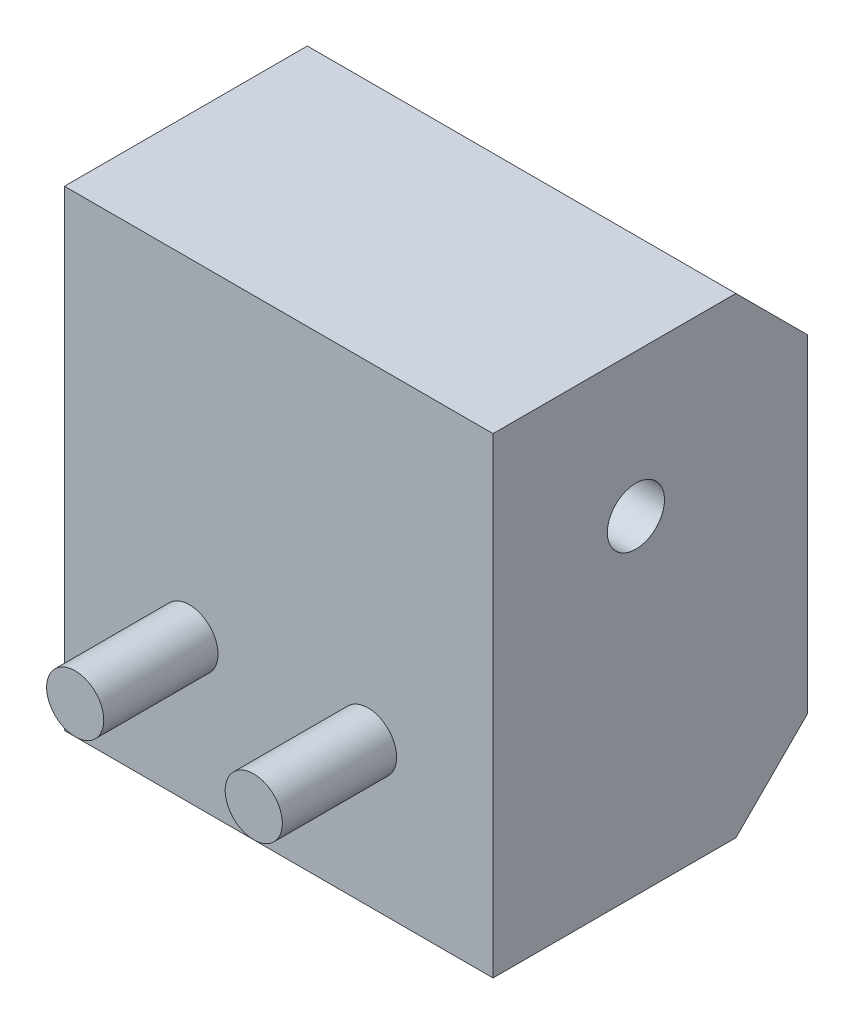
SolidWorks part; units mm, degrees
ref_plane "Alzado" through (0, 0, 0) normal (0, 0, 1) x (1, 0, 0)
ref_plane "Planta" through (0, 0, 0) normal (0, 1, 0) x (1, 0, 0)
ref_plane "Vista lateral" through (0, 0, 0) normal (1, 0, 0) x (0, 0, -1)
sketch "Croquis1" plane through (0, 0, 0) normal (0, 0, 1) x (1, 0, 0)
  line L1 (-15.1661, 12.0664) -> (14.8339, 12.0664)
  line L2 (-15.1661, 12.0664) -> (-15.1661, -20.9336)
  line L3 (-15.1661, -20.9336) -> (14.8339, -20.9336)
  line L4 (14.8339, 12.0664) -> (14.8339, -20.9336)
  dimension "D1" = 30
  dimension "D2" = 33
extrude "Saliente-Extruir1" add sketch "Croquis1" along normal blind 22
sketch "Croquis2" plane through (0, 0, 22) normal (0, 0, 1) x (1, 0, 0)
  line L0 (-15.1661, 12.0664) -> (-15.1661, -20.9336) construction
  line L3 (-15.1661, -20.9336) -> (14.8339, -20.9336) construction
  circle A0 centre (-6.4161, -10.9336) radius 2
  circle A1 centre (6.0839, -10.9336) radius 2
  point P8 (0, 0)
  dimension "D1" = 4
  dimension "D2" = 4
  dimension "D3" = 12.5
  dimension "D4" = 8.75
  dimension "D5" = 10
extrude "Saliente-Extruir2" add sketch "Croquis2" along normal blind 8
sketch "Croquis3" plane through (14.8339, 0, 0) normal (1, 0, 0) x (0, 0, -1)
  line L0 (-22, -20.9336) -> (-22, 12.0664) construction
  line L1 (-22, 12.0664) -> (0, 12.0664) construction
  circle A0 centre (-12, 2.0664) radius 2
  dimension "D1" = 4
  dimension "D2" = 10
  dimension "D3" = 10
chamfer "Chaflán1" distance 5 angle 45 1 edges at (-0.1661, 12.0664, 0)
chamfer "Chaflán2" distance 5 angle 45 1 edges at (-0.1661, -20.9336, 0)
extrude "Cortar-Extruir1" cut sketch "Croquis3" against normal blind 35
